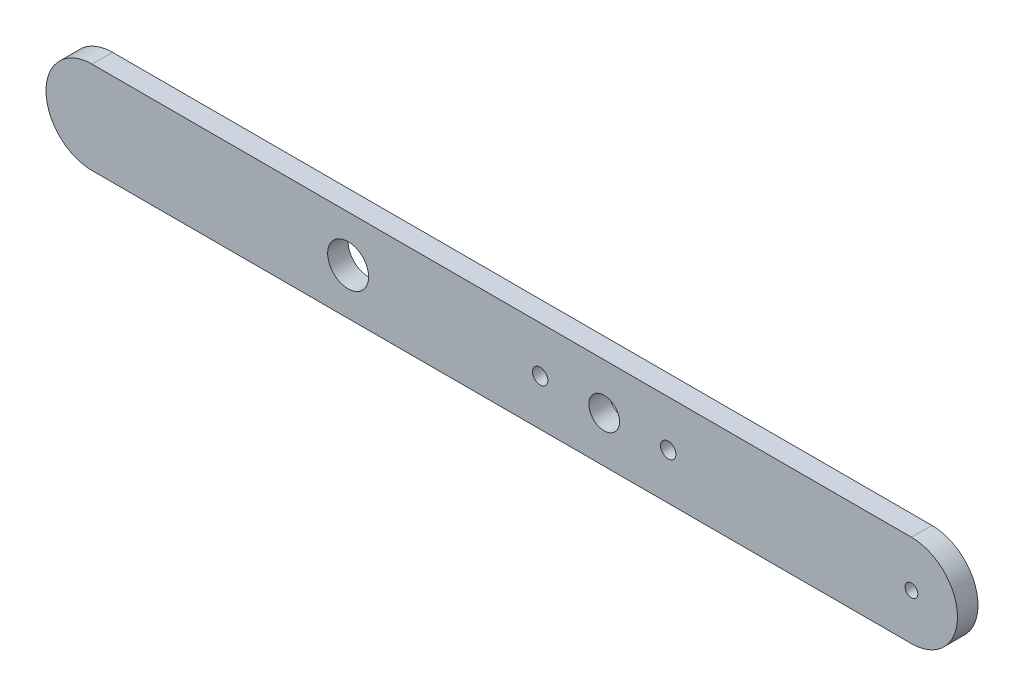
SolidWorks part; units mm, degrees
material "ﾊﾞﾙｻ"
ref_plane "正面" through (0, 0, 0) normal (0, 0, 1) x (1, 0, 0)
ref_plane "平面" through (0, 0, 0) normal (0, 1, 0) x (1, 0, 0)
ref_plane "右側面" through (0, 0, 0) normal (1, 0, 0) x (0, 0, -1)
sketch "ｽｹｯﾁ1" plane through (0, 0, 0) normal (0, 0, 1) x (1, 0, 0)
  line L0 (0, 0) -> (160, 0) construction
  line L1 (0, 9) -> (160, 9)
  line L2 (0, -9) -> (160, -9)
  arc A0 (0, 9) -> (0, -9) centre (0, 0) ccw
  arc A1 (160, -9) -> (160, 9) centre (160, 0) ccw
  circle A2 centre (160, 0) radius 1.25
  circle A3 centre (100, 0) radius 3
  circle A5 centre (50, 0) radius 4
  point P3 (80, 0)
  dimension "D2" = 2.5
  dimension "D3" = 9
  dimension "D4" = 6
  dimension "D6" = 8
  dimension "D7" = 50
  dimension "D1" = 60
  dimension "D5" = 100
extrude "ﾎﾞｽ - 押し出し1" add sketch "ｽｹｯﾁ1" along normal blind 4
sketch "ｽｹｯﾁ2" plane through (0, 0, 4) normal (0, 0, 1) x (1, 0, 0)
  line L0 (100, 0) -> (100, -9) construction
  line L1 (0, -9) -> (160, -9) construction
  line L2 (87.5, 0) -> (112.5, 0) construction
  circle A0 centre (112.5, 0) radius 1.5
  circle A1 centre (87.5, 0) radius 1.5
  dimension "D2" = 3
  dimension "D1" = 25
extrude "ｶｯﾄ - 押し出し1" cut sketch "ｽｹｯﾁ2" against normal through all
